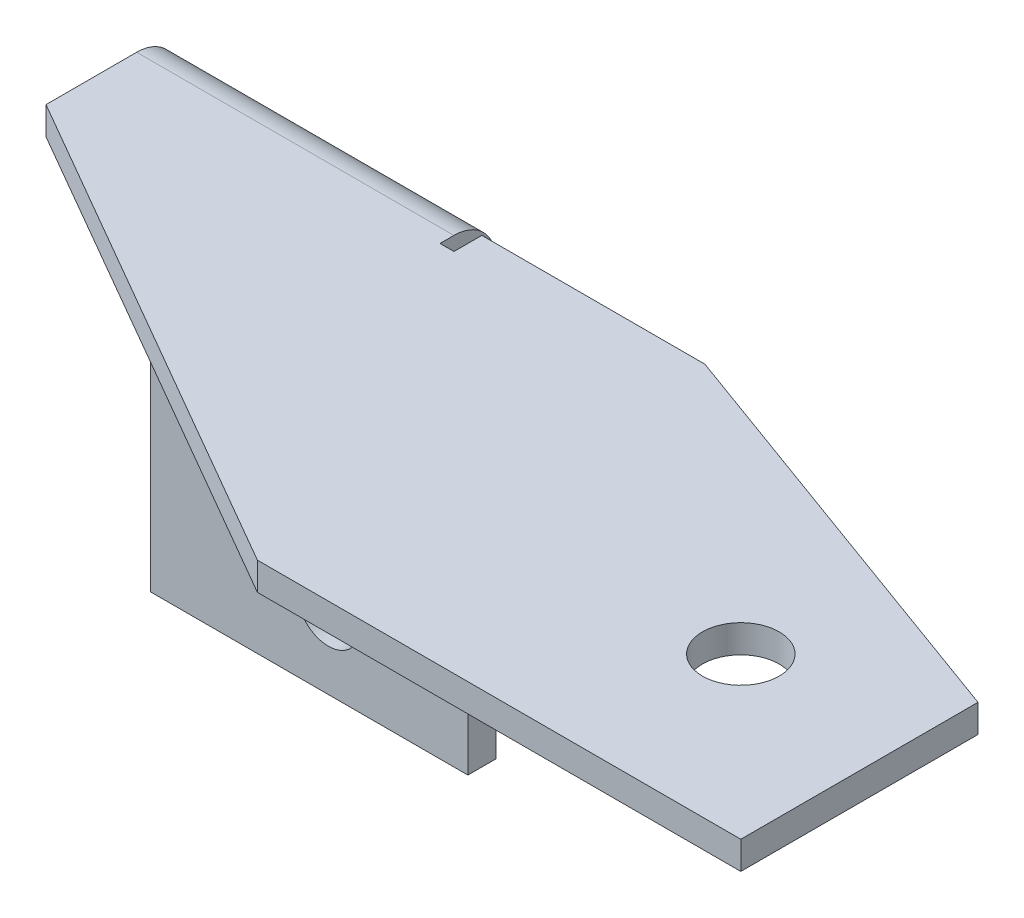
SolidWorks part; units mm, degrees
material "6061 合金"
ref_plane "前视基准面" through (0, 0, 0) normal (0, 0, 1) x (1, 0, 0)
ref_plane "上视基准面" through (0, 0, 0) normal (0, 1, 0) x (1, 0, 0)
ref_plane "右视基准面" through (0, 0, 0) normal (1, 0, 0) x (0, 0, -1)
other "Configuration Table"
sketch "草图1" plane through (0, 0, 0) normal (0, 1, 0) x (1, 0, 0)
  line L0 (0, 0) -> (39.7283, 0)
  line L1 (39.7283, 0) -> (70.5, -11.2)
  line L2 (70.5, -11.2) -> (70.5, -28.2)
  line L3 (70.5, -28.2) -> (35.8535, -28.2)
  line L4 (35.8535, -28.2) -> (0, -7.5)
  line L5 (0, -7.5) -> (0, 0)
  dimension "D1" = 7.5
  dimension "D2" = 70.5
  dimension "D3" = 28.2
  dimension "D4" = 160
  dimension "D5" = 120
  dimension "D6" = 17
extrude "凸台-拉伸1" add sketch "草图1" along normal blind 2
sketch "草图2" plane through (0, 2, 0) normal (0, 1, 0) x (1, 0, 0)
  line L0 (70.5, -28.2) -> (70.5, -11.2) construction
  line L1 (35.8535, -28.2) -> (70.5, -28.2) construction
  circle A0 centre (59, -16.7) radius 2.75
  dimension "D3" = 5.5
  dimension "D1" = 11.5
  dimension "D2" = 11.5
extrude "切除-拉伸1" cut sketch "草图2" against normal through all
sketch "草图3" plane through (0, 0, 0) normal (0, -1, 0) x (1, 0, 0)
  line L0 (0, 0) -> (22.7379, 0)
  line L1 (39.7283, 0) -> (0, 0) construction
  line L2 (22.7379, 0) -> (22.7379, -2)
  line L3 (22.7379, -2) -> (0, -2)
  line L4 (0, 0) -> (0, 7.5) construction
  line L5 (0, -2) -> (0, 0)
  dimension "D1" = 22.7379
  dimension "D2" = 2
extrude "凸台-拉伸2" add sketch "草图3" along normal blind 32 and the other way blind 2
sketch "草图4" plane through (0, 0, 0) normal (0, 0, -1) x (-1, 0, 0)
  line L0 (-12.7379, -32) -> (-12.7379, 2) construction
  line L1 (0, -32) -> (-22.7379, -32) construction
  line L2 (-39.7283, 2) -> (-22.7379, 2) construction
  line L3 (-22.7379, -32) -> (-22.7379, 0) construction
  line L4 (-12.7379, -26.75) -> (-12.7379, -21.25) construction
  line L5 (-14.9879, -26.75) -> (-14.9879, -21.25)
  line L6 (-10.4879, -26.75) -> (-10.4879, -21.25)
  line L7 (-12.7379, -12.25) -> (-12.7379, -6.75) construction
  line L8 (-14.9879, -12.25) -> (-14.9879, -6.75)
  line L9 (-10.4879, -12.25) -> (-10.4879, -6.75)
  arc A0 (-14.9879, -26.75) -> (-10.4879, -26.75) centre (-12.7379, -26.75) ccw
  arc A1 (-10.4879, -21.25) -> (-14.9879, -21.25) centre (-12.7379, -21.25) ccw
  arc A2 (-14.9879, -12.25) -> (-10.4879, -12.25) centre (-12.7379, -12.25) ccw
  arc A3 (-10.4879, -6.75) -> (-14.9879, -6.75) centre (-12.7379, -6.75) ccw
  point P10 (-12.7379, -24)
  point P15 (-12.7379, -9.5)
  point P22 (-12.7379, -29)
  dimension "D2" = 4.5
  dimension "D7" = 9
  dimension "D1" = 10
  dimension "D3" = 4.5
  dimension "D4" = 5.5
  dimension "D5" = 5.5
  dimension "D6" = 3
extrude "切除-拉伸2" cut sketch "草图4" along normal through all
sketch "草图7" plane through (0, 2, 0) normal (0, 1, 0) x (1, 0, 0)
  line L0 (22.7379, 0) -> (22.7379, -2)
  line L1 (22.7379, -2) -> (23.7379, -2)
  line L2 (23.7379, -2) -> (23.7379, 0)
  line L3 (39.7283, 0) -> (22.7379, 0) construction
  line L4 (23.7379, 0) -> (22.7379, 0)
  dimension "D1" = 2
  dimension "D2" = 1
extrude "切除-拉伸3" cut sketch "草图7" against normal blind 2
fillet "圆角1" radius 3 1 edges at (11.369, 2, -2)
fillet "圆角2" radius 1 1 edges at (11.369, 0, 0)
